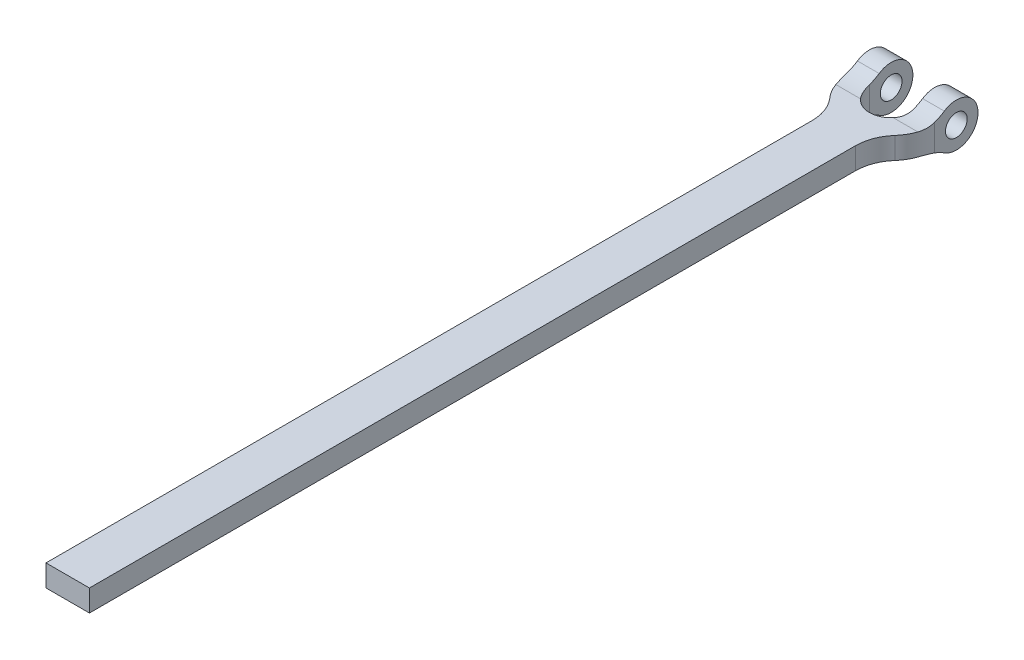
SolidWorks part; units mm, degrees
ref_plane "Front Plane" through (0, 0, 0) normal (0, 0, 1) x (1, 0, 0)
ref_plane "Top Plane" through (0, 0, 0) normal (0, 1, 0) x (1, 0, 0)
ref_plane "Right Plane" through (0, 0, 0) normal (1, 0, 0) x (0, 0, -1)
sketch "Sketch1" plane through (0, 0, 0) normal (0, 1, 0) x (1, 0, 0)
  line L0 (-5, 90) -> (-5, 100)
  line L1 (10, -100) -> (-10, -100)
  line L2 (10, -100) -> (10, 100)
  line L3 (10, 100) -> (-10, 100)
  line L4 (-10, -100) -> (-10, 100)
  line L6 (-5, 76.7712) -> (-5, -100)
  line L7 (-5, -100) -> (5, -100)
  line L8 (5, 76.7712) -> (5, -100)
  line L9 (5, 90) -> (5, 100)
  arc A0 (7.5, 83.3856) -> (-7.5, 83.3856) centre (0, 90) ccw
  circle A1 centre (0, 90) radius 5
  arc A2 (-7.5, 83.3856) -> (-5, 76.7712) centre (-15, 76.7712) cw
  arc A3 (7.5, 83.3856) -> (5, 76.7712) centre (15, 76.7712) ccw
  point P0 (0, 0)
  dimension "D3" = 20
  dimension "D5" = 10
  dimension "D6" = 10
  dimension "D7" = 10
  dimension "D1" = 200
  dimension "D2" = 20
  dimension "D4" = 10
extrude "Boss-Extrude1" add sketch "Sketch1" along normal blind 10 contours A3 A0 L9 A1 L0 A2 L6 L1 L8 | A0 L2 L3 L9 | A0 L0 L3 L4
sketch "Sketch2" plane through (-10, 0, 0) normal (-1, 0, 0) x (0, 0, 1)
  line L0 (-95, 10) -> (-95, 0) construction
  line L1 (-76.7712, 0) -> (100, 0) construction
  line L2 (-86.7113, 7.5) -> (99.5575, 7.5)
  line L3 (-100, 5) -> (-93.4802, 5) construction
  line L4 (-95, 7.5) -> (-95, 2.5)
  line L5 (-86.7113, 2.5) -> (99.5575, 2.5)
  line L6 (99.5575, 7.5) -> (99.5575, 2.5)
  line L7 (-83.3856, 0) -> (-76.7712, 0) construction
  line L8 (-90, 0) -> (-83.3856, 0) construction
  line L9 (-90, 0) -> (-100, 0) construction
  line L10 (-90, 0) -> (-100, 0) construction
  line L11 (-100, 10) -> (-100, 0) construction
  line L12 (-76.7712, 10) -> (-83.3856, 10) construction
  line L13 (-90, 10) -> (-100, 10) construction
  line L14 (-83.3856, 10) -> (-90, 10) construction
  line L15 (-76.7712, 0) -> (100, 0)
  line L16 (-83.3856, 0) -> (-76.7712, 0)
  line L17 (-90, 0) -> (-83.3856, 0)
  line L18 (-90, 0) -> (-100, 0)
  line L19 (-90, 0) -> (-100, 0)
  line L20 (-100, 10) -> (-100, 0)
  line L21 (-76.7712, 10) -> (-83.3856, 10)
  line L22 (-90, 10) -> (-100, 10)
  line L23 (-83.3856, 10) -> (-90, 10)
  line L24 (100, 10) -> (100, 0) construction
  line L25 (-76.7712, 10) -> (100, 10) construction
  line L26 (100, 10) -> (100, 0)
  line L27 (-76.7712, 10) -> (100, 10)
  arc A0 (-92.2377, 9.1658) -> (-92.2377, 0.8342) centre (-95, 5) ccw
  circle A1 centre (-95, 5) radius 2.5
  arc A2 (-86.7113, 7.5) -> (-92.2377, 9.1658) centre (-86.7113, 17.5) cw
  arc A3 (-92.2377, 0.8342) -> (-86.7113, 2.5) centre (-86.7113, -7.5) cw
  line M3 (-100, 0) -> (-90, 0)
  line M4 (-90, 0) -> (-90, 10)
  line M5 (-90, 10) -> (-100, 10)
  line M6 (-100, 10) -> (-100, 0)
  dimension "D1" = 9.9969
  dimension "D2" = 5
  dimension "D3" = 10
  dimension "D4" = 194.5575
extrude "Cut-Extrude5" cut sketch "Sketch2" against normal through all contours A3 A0 A2 M4 M5 M6 M3 | A3 L17 L16 L15 L26 L27 L21 L23 A2 L2 L6 L5 M4 | L4 A1 | L4 A1
